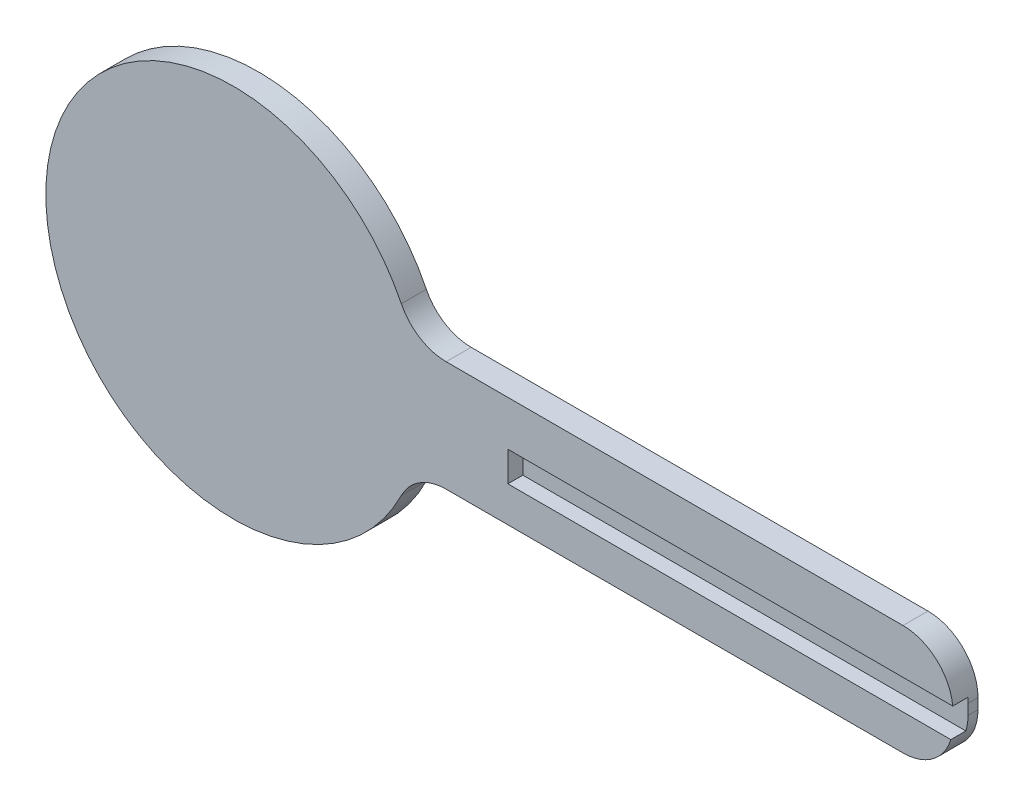
SolidWorks part; units mm, degrees
ref_plane "Front Plane" through (0, 0, 0) normal (0, 0, 1) x (1, 0, 0)
ref_plane "Top Plane" through (0, 0, 0) normal (0, 1, 0) x (1, 0, 0)
ref_plane "Right Plane" through (0, 0, 0) normal (1, 0, 0) x (0, 0, -1)
sketch "Sketch1" plane through (0, 0, 0) normal (0, 0, 1) x (1, 0, 0)
  line L1 (85.1701, 22.0839) -> (267.9397, 22.0839)
  line L3 (85.1701, -22.0839) -> (267.9397, -22.0839)
  line L4 (287.9397, 2.0839) -> (287.9397, -2.0839)
  arc A0 (67.2396, 33.2241) -> (67.2396, -33.2241) centre (0, 0) ccw
  arc A1 (267.9397, -22.0839) -> (287.9397, -2.0839) centre (267.9397, -2.0839) ccw
  arc A2 (267.9397, 22.0839) -> (287.9397, 2.0839) centre (267.9397, 2.0839) cw
  arc A3 (85.1701, -22.0839) -> (67.2396, -33.2241) centre (85.1701, -42.0839) ccw
  arc A4 (85.1701, 22.0839) -> (67.2396, 33.2241) centre (85.1701, 42.0839) cw
  point P3 (75, 0)
  dimension "D1" = 150
  dimension "D2" = 20
extrude "Boss-Extrude1" add sketch "Sketch1" along normal blind 10
sketch "Sketch2" plane through (0, 0, 10) normal (0, 0, 1) x (1, 0, 0)
  line L0 (109.8484, 4.1166) -> (109.8484, -7.8834)
  line L1 (109.8484, 4.1166) -> (278.7778, 4.1166)
  line L3 (109.8484, -7.8834) -> (278.7778, -7.8834)
  line L4 (278.7778, 4.1166) -> (278.7778, -7.8834)
  line L5 (109.8484, 2.032) -> (278.7778, -7.8834) construction
  line L6 (109.8484, -5.7987) -> (278.7778, 4.1166) construction
  point P0 (176.5549, -1.8834)
  dimension "D1" = 12
extrude "Cut-Extrude1" cut sketch "Sketch2" against normal blind 6
sketch "Sketch3" plane through (0, 0, 10) normal (0, 0, 1) x (1, 0, 0)
  line L0 (278.7778, 4.1166) -> (358.7377, 4.1166)
  line L1 (358.7377, 4.1166) -> (358.7377, -7.8834)
  line L2 (358.7377, -7.8834) -> (278.7778, -7.8834)
  line L3 (278.7778, -7.8834) -> (278.7778, 4.1166)
extrude "Cut-Extrude2" cut sketch "Sketch3" against normal blind 6
